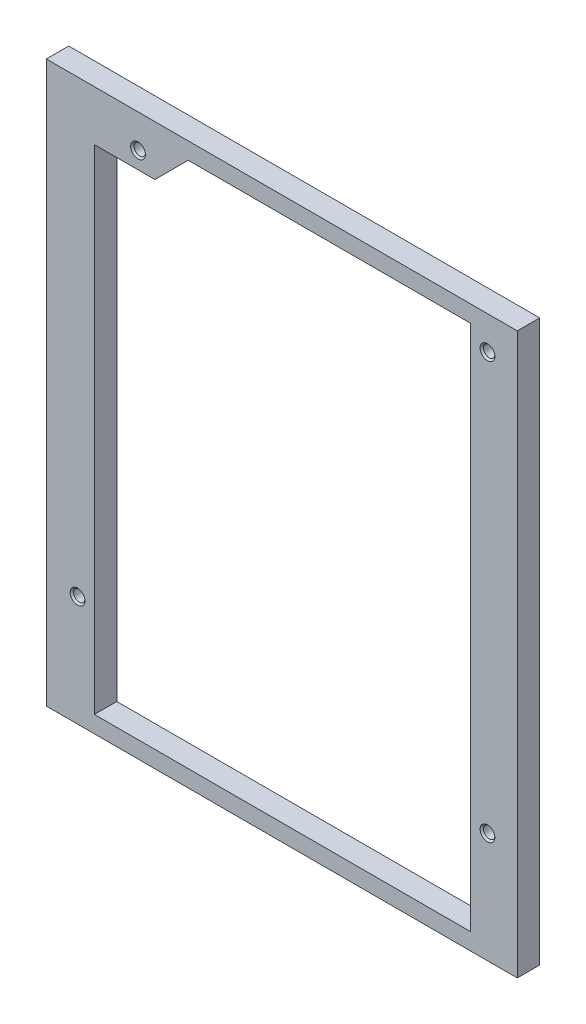
SolidWorks part; units mm, degrees
ref_plane "Front Plane" through (0, 0, 0) normal (0, 0, 1) x (1, 0, 0)
ref_plane "Top Plane" through (0, 0, 0) normal (0, 1, 0) x (1, 0, 0)
ref_plane "Right Plane" through (0, 0, 0) normal (1, 0, 0) x (0, 0, -1)
ref_plane "Plane3" through (0, 0, 9.525) normal (0, 0, 1) x (1, 0, 0)
sketch "Mini ITX" plane through (0, 0, 9.525) normal (0, 0, 1) x (1, 0, 0)
  line L0 (-85, 85) -> (-85, -85) construction
  line L3 (-85, 85) -> (85, 85) construction
  line L4 (85, -85) -> (85, 85) construction
  line L9 (-85, -85) -> (85, -85) construction
  line L10 (-85, 87.5654) -> (-85, -71.4386) construction
  line L14 (-85, -71.4386) -> (-85, -112.0786) construction
  point P0 (-85, 0)
  point P4 (0, 85)
  point P12 (-51.9797, 78.74)
  point P13 (-74.8397, -78.74)
  point P14 (80.1003, -78.74)
  point P17 (80.1003, 78.74)
  dimension "D1" = 170
  dimension "D2" = 22.86
  dimension "D3" = 154.94
  dimension "D4" = 157.48
  dimension "D5" = 4.8997
  dimension "D6" = 6.26
  dimension "D7" = 2.5654
  dimension "D8" = 159.004
  dimension "D9" = 40.64
ref_plane "Plane4" through (0, 0, 0.5) normal (0, 0, 1) x (1, 0, 0)
sketch "Sketch8" plane through (0, 0, 0.5) normal (0, 0, 1) x (1, 0, 0)
  line L0 (-85, 85) -> (-85, -85) construction
  line L1 (-96.811, -122.2386) -> (3.189, -122.2386) construction
  line L2 (-96.811, -122.2386) -> (-96.811, -185.7386) construction
  line L3 (-96.811, -185.7386) -> (3.189, -185.7386) construction
  line L4 (3.189, -122.2386) -> (3.189, -185.7386) construction
  line L5 (-85, -85) -> (85, -85) construction
  dimension "D1" = 11.811
  dimension "D2" = 10.16
  dimension "D3" = 63.5
  dimension "D4" = 100
  dimension "D5" = 37.2386
ref_plane "Plane2" through (-96.811, 0, 0) normal (1, 0, 0) x (0, 0, -1)
sketch "Sketch6" plane through (-96.811, 0, 0) normal (1, 0, 0) x (0, 0, -1)
  line L1 (-125.5, -122.2386) -> (-0.5, -122.2386) construction
  line L2 (-125.5, -122.2386) -> (-125.5, -185.7386) construction
  line L3 (-125.5, -185.7386) -> (-0.5, -185.7386) construction
  line L4 (-0.5, -122.2386) -> (-0.5, -185.7386) construction
  line L5 (-125.5, -128.2386) -> (-119.5, -128.2386) construction
  line L6 (-119.5, -128.2386) -> (-119.5, -122.2386) construction
  line L7 (-6.5, -185.7386) -> (-6.5, -179.7386) construction
  line L8 (-6.5, -179.7386) -> (-0.5, -179.7386) construction
  point P5 (-6.5, -128.2386)
  point P6 (-6.5, -179.7386)
  point P7 (-119.5, -179.7386)
  point P14 (-119.5, -128.2386)
  point P17 (-125.5, -153.9886)
  point P20 (-6.5, -153.9886)
  point P22 (-119.5, -153.9886)
  dimension "D1" = 125
  dimension "D2" = 6
sketch "Sketch3" plane through (0, 0, 0) normal (0, 0, 1) x (1, 0, 0)
  line L0 (-85, 85) -> (85, 85) construction
  line L1 (-86.651, 91.35) -> (91.35, 91.35)
  line L2 (-86.651, 91.35) -> (-86.651, -120.4686)
  line L3 (-86.651, -120.4686) -> (91.35, -120.4686)
  line L4 (91.35, 91.35) -> (91.35, -120.4686)
  line L5 (-33.0197, 85) -> (73.7503, 85)
  line L7 (-68.4897, -114.1186) -> (73.7503, -114.1186)
  line L8 (73.7503, 85) -> (73.7503, -114.1186)
  line L10 (-85, 85) -> (-85, -85) construction
  line L11 (-68.4897, 72.39) -> (-68.4897, -114.1186)
  line L12 (85, -85) -> (85, 85) construction
  line L13 (-96.811, -122.2386) -> (3.189, -122.2386) construction
  line L16 (-68.4897, 72.39) -> (-45.6297, 72.39)
  line L17 (-45.6297, 72.39) -> (-33.0197, 85)
  dimension "D1" = 6.35
  dimension "D2" = 1.651
  dimension "D3" = 6.35
  dimension "D4" = 6.35
  dimension "D5" = 6.35
  dimension "D6" = 6.35
  dimension "D7" = 6.35
  dimension "D8" = 1.77
  dimension "D9" = 6.35
  dimension "D10" = 45
  dimension "D11" = 6.35
  dimension "D12" = 211.8186
extrude "Boss-Extrude1" add sketch "Sketch3" against normal blind 8.4667
sketch "Sketch4" plane through (0, 0, 0) normal (0, 0, -1) x (-1, 0, 0)
  point P0 (51.9797, 78.74)
  point P1 (74.8397, -78.74)
  point P3 (-80.1003, -78.74)
  point P5 (-80.1003, 78.74)
hole_wizard "#18 (0.1695) Diameter Hole1" positions "Sketch4" profile "Sketch5" hole size "#18" standard "ANSI Inch" end condition through all
sketch "Sketch5" plane through (-51.9797, 78.74, 0) normal (1, 0, 0) x (0, -1, 0)
  line L0 (0, 0) -> (0, 8.4667)
  line L1 (0, 8.4667) -> (2.1526, 8.4667)
  line L2 (2.1526, 8.4667) -> (2.1526, 0.635)
  line L3 (2.1526, 0.635) -> (2.7876, 0)
  line L5 (2.7876, 0) -> (0, 0)
  line L6 (-2.1526, 0.635) -> (-2.7876, 0) construction
  line L11 (0, -6.35) -> (0, 107.95) construction
  dimension "Thru Hole Dia." = 4.3053
  dimension "Thru Hole Depth" = 8.4667
  dimension "Near C'Sink Dia." = 5.5753
  dimension "Near C'Sink Angle" = 90
sketch "Sketch9" plane through (-86.651, 0, 0) normal (-1, 0, 0) x (0, 0, 1)
  line L0 (-4.2333, -65.0886) -> (-1.0583, -68.2636)
  line L1 (-4.2333, -65.0886) -> (-7.4083, -68.2636)
  line L2 (-1.0583, -68.2636) -> (-4.2333, -71.4386)
  line L3 (-7.4083, -68.2636) -> (-4.2333, -71.4386)
  line L4 (-4.2333, -65.0886) -> (-4.2333, -71.4386) construction
  line L5 (-1.0583, -68.2636) -> (-7.4083, -68.2636) construction
  line L6 (-4.2333, 90.2917) -> (-1.0583, 87.1167)
  line L7 (-4.2333, 90.2917) -> (-7.4083, 87.1167)
  line L8 (-1.0583, 87.1167) -> (-4.2333, 83.9417)
  line L9 (-7.4083, 87.1167) -> (-4.2333, 83.9417)
  line L10 (-4.2333, 90.2917) -> (-4.2333, 83.9417) construction
  line L11 (-1.0583, 87.1167) -> (-7.4083, 87.1167) construction
  line L12 (-8.4667, 91.35) -> (0, 91.35) construction
  line L13 (0, 91.35) -> (0, -120.4686) construction
  point P1 (-4.2333, -68.2636)
  point P2 (-4.2333, 87.1167)
  point P15 (-4.2333, -66.9348)
  point P16 (0, 0)
  point P17 (-4.2333, -64.4878)
  point P20 (-4.2333, -71.1626)
  point P22 (0, 0)
  dimension "D1" = 6.35
  dimension "D2" = 4.2333
  dimension "D3" = 4.2333
extrude "Cut-Extrude1" cut sketch "Sketch9" against normal blind 5.08
sketch "Sketch10" plane through (0, -120.4686, 0) normal (0, -1, 0) x (1, 0, 0)
  line L0 (-85.5927, -4.2333) -> (-82.4177, -1.0583)
  line L1 (-85.5927, -4.2333) -> (-82.4177, -7.4083)
  line L2 (-82.4177, -1.0583) -> (-79.2427, -4.2333)
  line L3 (-82.4177, -7.4083) -> (-79.2427, -4.2333)
  line L4 (-85.5927, -4.2333) -> (-79.2427, -4.2333) construction
  line L5 (-82.4177, -1.0583) -> (-82.4177, -7.4083) construction
  line L6 (83.9417, -4.2333) -> (87.1167, -1.0583)
  line L7 (83.9417, -4.2333) -> (87.1167, -7.4083)
  line L8 (87.1167, -1.0583) -> (90.2917, -4.2333)
  line L9 (87.1167, -7.4083) -> (90.2917, -4.2333)
  line L10 (83.9417, -4.2333) -> (90.2917, -4.2333) construction
  line L11 (87.1167, -1.0583) -> (87.1167, -7.4083) construction
  line L12 (91.35, -8.4667) -> (91.35, 0) construction
  line L13 (-86.651, 0) -> (91.35, 0) construction
  line L14 (-86.651, -8.4667) -> (-86.651, 0) construction
  point P1 (-82.4177, -4.2333)
  point P2 (87.1167, -4.2333)
  dimension "D1" = 6.35
  dimension "D2" = 4.2333
  dimension "D3" = 4.2333
  dimension "D4" = 4.2333
extrude "Cut-Extrude2" cut sketch "Sketch10" against normal blind 5.08
chamfer "Chamfer1" distance 0.635 angle 45 32 edges at (-81.571, 88.7042, -2.6458) (-81.571, 85.5292, -2.6458) (-81.571, 85.5292, -5.8208) (-81.571, 88.7042, -5.8208) (-81.571, -66.6761, -2.6458) (-81.571, -69.8511, -2.6458) (-81.571, -69.8511, -5.8208) (-81.571, -66.6761, -5.8208) (-86.651, 85.5292, -2.6458) (-86.651, 85.5292, -5.8208) (-86.651, 88.7042, -2.6458) (-86.651, 88.7042, -5.8208) (-86.651, -66.6761, -2.6458) (-86.651, -69.8511, -2.6458) (-86.651, -69.8511, -5.8208) (-86.651, -66.6761, -5.8208) (85.5292, -115.3886, -2.6458) (88.7042, -115.3886, -2.6458) (88.7042, -115.3886, -5.8208) (85.5292, -115.3886, -5.8208) (-84.0052, -115.3886, -2.6458) (-80.8302, -115.3886, -2.6458) (-80.8302, -115.3886, -5.8208) (-84.0052, -115.3886, -5.8208) (85.5292, -120.4686, -5.8208) (88.7042, -120.4686, -5.8208) (88.7042, -120.4686, -2.6458) (85.5292, -120.4686, -2.6458) (-84.0052, -120.4686, -5.8208) (-80.8302, -120.4686, -5.8208) (-80.8302, -120.4686, -2.6458) (-84.0052, -120.4686, -2.6458)
